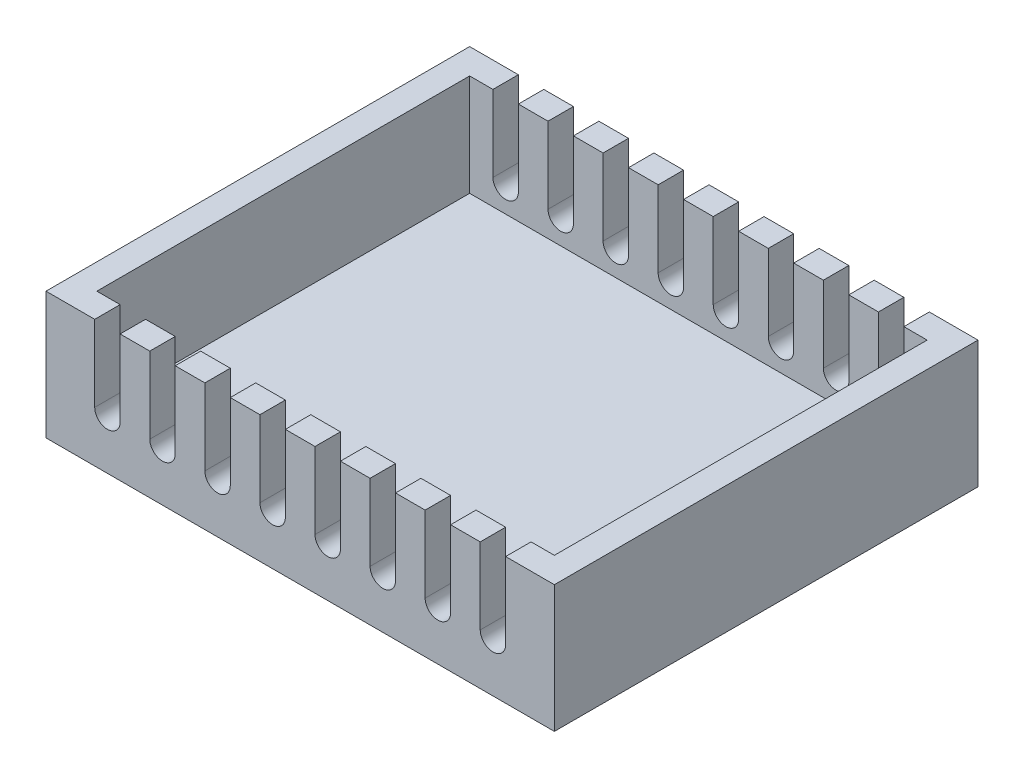
SolidWorks part; units mm, degrees
ref_plane "Front Plane" through (0, 0, 0) normal (0, 0, 1) x (1, 0, 0)
ref_plane "Top Plane" through (0, 0, 0) normal (0, 1, 0) x (1, 0, 0)
ref_plane "Right Plane" through (0, 0, 0) normal (1, 0, 0) x (0, 0, -1)
sketch "Sketch1" plane through (0, 0, 0) normal (0, 0, 1) x (1, 0, 0)
  line L1 (-4.1275, -1.905) -> (4.1275, -1.905) construction
  line L2 (-38.1, -9.525) -> (38.1, -9.525)
  line L3 (-38.1, -9.525) -> (-38.1, 9.525)
  line L4 (-38.1, 9.525) -> (38.1, 9.525)
  line L5 (38.1, -9.525) -> (38.1, 9.525)
  line L6 (-38.1, -9.525) -> (38.1, 9.525) construction
  line L7 (-38.1, 9.525) -> (38.1, -9.525) construction
  line L8 (0, -55) -> (0, 55) construction
  line L9 (-30.7975, -1.905) -> (-30.7975, 9.525)
  line L10 (-26.9875, -1.905) -> (-26.9875, 9.525)
  line L11 (-22.5425, -1.905) -> (-22.5425, 9.525)
  line L12 (-18.7325, -1.905) -> (-18.7325, 9.525)
  line L13 (-14.2875, -1.905) -> (-14.2875, 9.525)
  line L14 (-10.4775, -1.905) -> (-10.4775, 9.525)
  line L15 (-6.0325, -1.905) -> (-6.0325, 9.525)
  line L16 (-2.2225, -1.905) -> (-2.2225, 9.525)
  line L17 (2.2225, -1.905) -> (2.2225, 9.525)
  line L18 (6.0325, -1.905) -> (6.0325, 9.525)
  line L19 (10.4775, -1.905) -> (10.4775, 9.525)
  line L20 (14.2875, -1.905) -> (14.2875, 9.525)
  line L21 (18.7325, -1.905) -> (18.7325, 9.525)
  line L22 (22.5425, -1.905) -> (22.5425, 9.525)
  line L23 (26.9875, -1.905) -> (26.9875, 9.525)
  line L24 (30.7975, -1.905) -> (30.7975, 9.525)
  arc A1 (-30.7975, -1.905) -> (-26.9875, -1.905) centre (-28.8925, -1.905) ccw
  arc A2 (-22.5425, -1.905) -> (-18.7325, -1.905) centre (-20.6375, -1.905) ccw
  arc A3 (-14.2875, -1.905) -> (-10.4775, -1.905) centre (-12.3825, -1.905) ccw
  arc A4 (-5.9883, -1.4971) -> (-2.2225, -1.905) centre (-4.1275, -1.905) ccw
  arc A5 (2.2225, -1.905) -> (5.9883, -1.4971) centre (4.1275, -1.905) ccw
  arc A6 (10.4775, -1.905) -> (14.2875, -1.905) centre (12.3825, -1.905) ccw
  arc A7 (18.7325, -1.905) -> (22.5425, -1.905) centre (20.6375, -1.905) ccw
  arc A8 (26.9875, -1.905) -> (30.7975, -1.905) centre (28.8925, -1.905) ccw
  point P0 (0, 0)
  point P8 (0, -1.905)
  dimension "D1" = 3.81
  dimension "D2" = 76.2
  dimension "D3" = 19.05
  dimension "D5" = 7.62
  dimension "D6" = 8.255
  dimension "D4" = 8
extrude "Boss-Extrude1" add sketch "Sketch1" along normal blind 63.5 contours A8 L23 L4 L22 A7 L21 L20 A6 L19 L18 A5 L17 L16 A4 L15 L14 A3 L13 L12 A2 L11 L10 A1 L9 L3 L2 L5 L24
sketch "Sketch2" plane through (0, -9.525, 0) normal (0, -1, 0) x (1, 0, 0)
  line L8 (-34.29, 3.81) -> (34.29, 3.81)
  line L9 (34.29, 3.81) -> (34.29, 59.69)
  line L10 (34.29, 59.69) -> (-34.29, 59.69)
  line L11 (-34.29, 59.69) -> (-34.29, 3.81)
  line L12 (-34.29, 3.81) -> (34.29, 3.81)
  line L13 (34.29, 3.81) -> (34.29, 59.69)
  line L14 (34.29, 59.69) -> (-34.29, 59.69)
  line L15 (-34.29, 59.69) -> (-34.29, 3.81)
  dimension "D1" = 3.81
extrude "Cut-Extrude2" cut sketch "Sketch2" against normal up to next from offset 3.81
